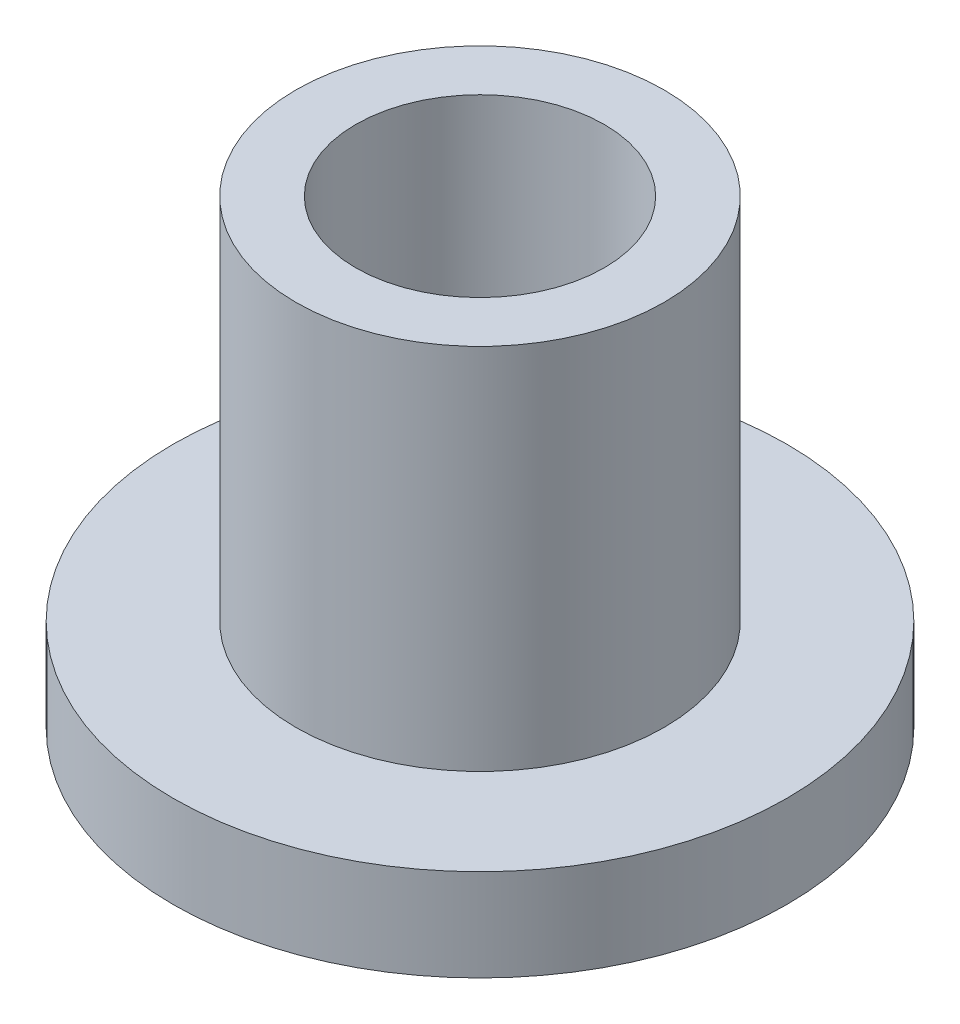
SolidWorks part; units mm, degrees
ref_plane "Plano frontal" through (0, 0, 0) normal (0, 0, 1) x (1, 0, 0)
ref_plane "Plano superior" through (0, 0, 0) normal (0, 1, 0) x (1, 0, 0)
ref_plane "Plano direito" through (0, 0, 0) normal (1, 0, 0) x (0, 0, -1)
sketch "Esboço1" plane through (0, 0, 0) normal (0, 1, 0) x (1, 0, 0)
  circle A0 centre (0, 0) radius 10
  dimension "D1" = 20
extrude "Ressalto-extrusão1" add sketch "Esboço1" along normal blind 3
sketch "Esboço2" plane through (0, 3, 0) normal (0, 1, 0) x (1, 0, 0)
  circle A0 centre (0, 0) radius 6
  dimension "D1" = 12
extrude "Ressalto-extrusão2" add sketch "Esboço2" along normal blind 12
sketch "Esboço3" plane through (0, 15, 0) normal (0, 1, 0) x (1, 0, 0)
  circle A0 centre (0, 0) radius 4.05
  dimension "D1" = 8.1
extrude "Corte-extrusão1" cut sketch "Esboço3" against normal through all
